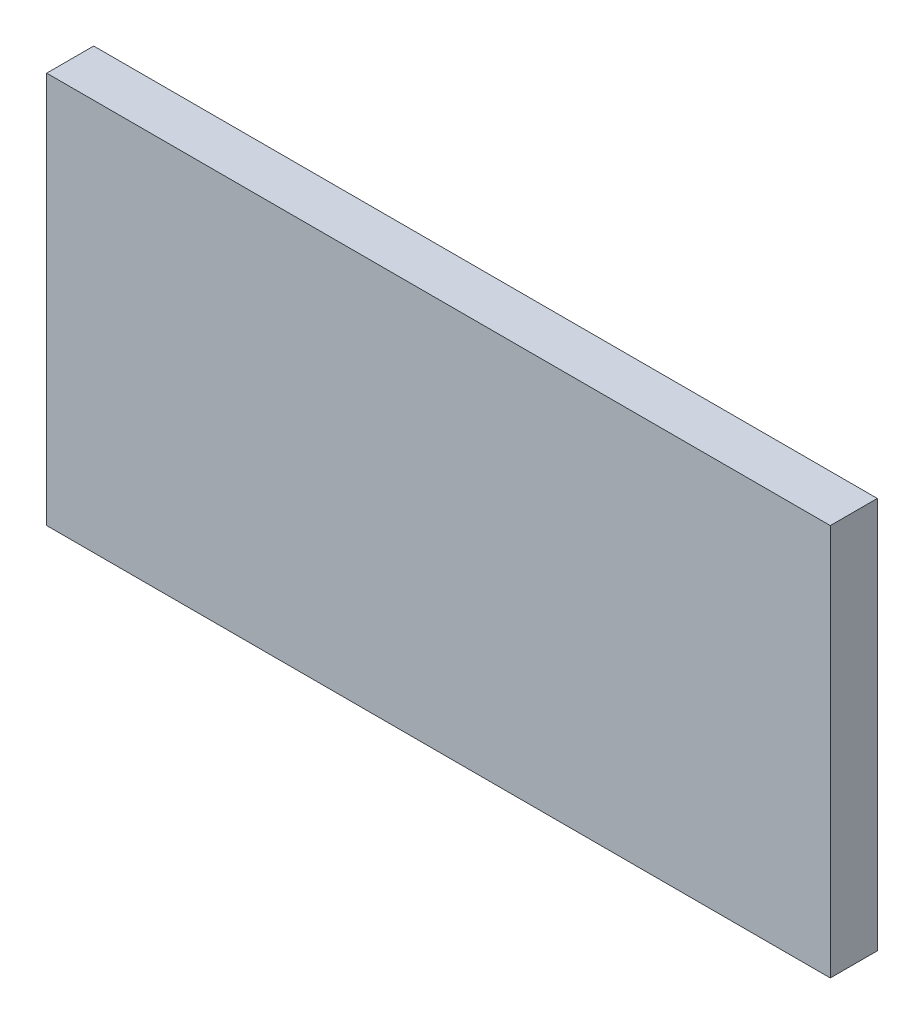
SolidWorks part; units mm, degrees
material "Faia"
ref_plane "Plano frontal" through (0, 0, 0) normal (0, 0, 1) x (1, 0, 0)
ref_plane "Plano superior" through (0, 0, 0) normal (0, 1, 0) x (1, 0, 0)
ref_plane "Plano direito" through (0, 0, 0) normal (1, 0, 0) x (0, 0, -1)
sketch "Esboço1" plane through (0, 0, 0) normal (0, 0, 1) x (1, 0, 0)
  line L1 (0, 0) -> (300, 0)
  line L2 (0, 0) -> (0, 150)
  line L3 (0, 150) -> (300, 150)
  line L4 (300, 0) -> (300, 150)
  dimension "D1" = 300
  dimension "D2" = 150
extrude "Ressalto-extrusão1" add sketch "Esboço1" along normal blind 18
